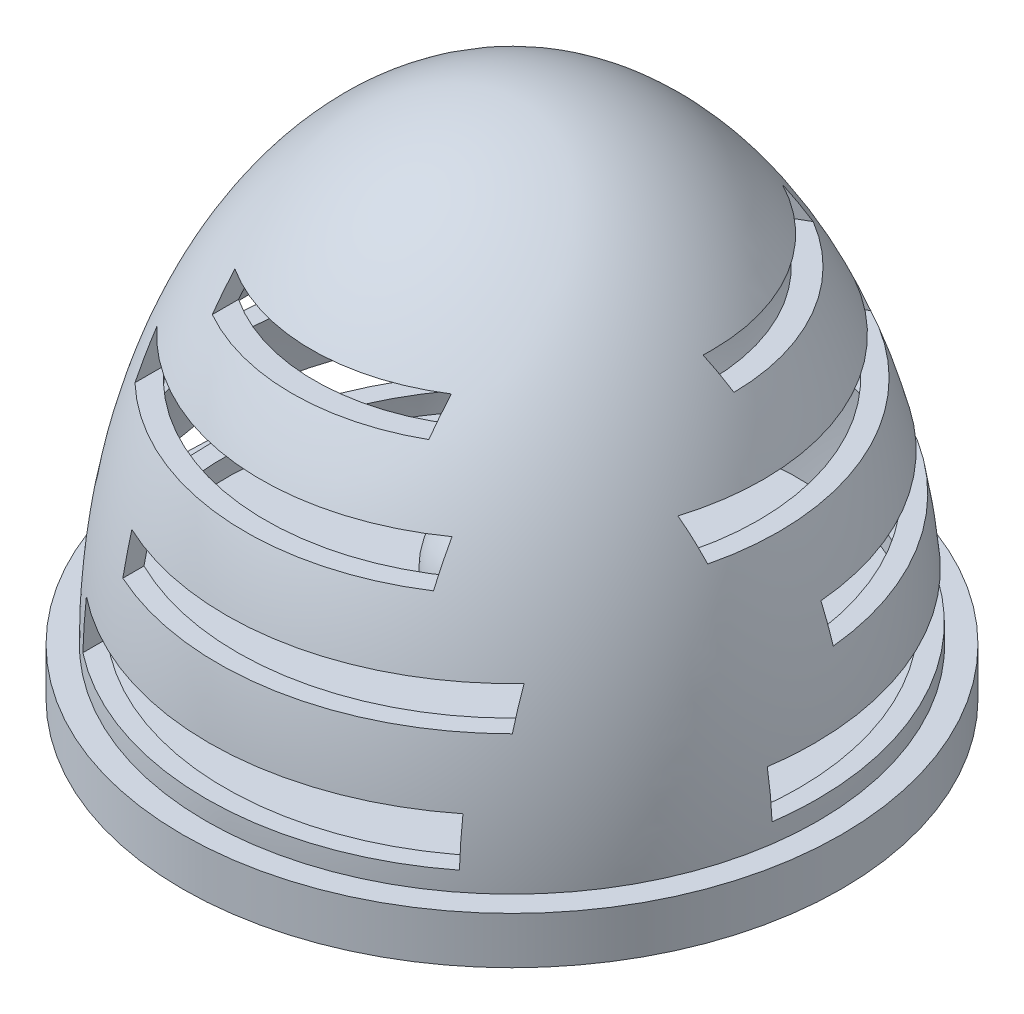
SolidWorks part; units mm, degrees
ref_plane "Piano frontale" through (0, 0, 0) normal (0, 0, 1) x (1, 0, 0)
ref_plane "Piano superiore" through (0, 0, 0) normal (0, 1, 0) x (1, 0, 0)
ref_plane "Piano destro" through (0, 0, 0) normal (1, 0, 0) x (0, 0, -1)
sketch "Schizzo1" plane through (0, 0, 0) normal (0, 1, 0) x (1, 0, 0)
  circle A0 centre (0, 0) radius 35
  dimension "D1" = 70
extrude "Estrusione-Estrusione1" add sketch "Schizzo1" along normal blind 5
sketch "Schizzo3" plane through (0, 5, 0) normal (0, 1, 0) x (1, 0, 0)
  line L0 (0, 49.3841) -> (0, -53.0263) construction
  line L1 (-54.1811, 0) -> (49.0863, 0) construction
  circle A0 centre (0, 0) radius 32.5
  dimension "D1" = 65
sketch "Schizzo4" plane through (0, 0, 0) normal (0, 0, 1) x (1, 0, 0)
  line L0 (32.5, 5) -> (-32.5, 5) construction
  line L1 (-54.1811, 5) -> (49.0863, 5) construction
  line L2 (0, 55) -> (0, 53)
  line L3 (30.5, 5) -> (32.5, 5)
  ellipse E0 centre (0, 5) end of major axis (0, 55) minor radius 32.5 (0, 55) -> (32.5, 5) cw
  spline S0 degree 1 poles (0, 53) (30.5, 5) knots 0 0 1 1 construction
  spline S1 degree 3 poles (0, 53) (1.9404, 53) (5.7713, 52.4189) (11.4211, 49.7948) (16.7188, 45.4458) (21.4383, 39.4955) (25.3526, 32.1643) (28.2812, 23.738) (30.0917, 14.569) (30.5, 8.1725) (30.5, 5) knots -1.570796 -1.570796 -1.570796 -1.570796 -1.374447 -1.178097 -0.981748 -0.785398 -0.589049 -0.392699 -0.19635 0 0 0 0
  dimension "D1" = 2
sketch "Schizzo6" plane through (0, 0, 0) normal (0, 0, 1) x (1, 0, 0)
  line L0 (0, 59.2821) -> (0, -7.287) construction
  line L1 (0, 23.503) -> (0, 5)
  arc A0 (0, 5) -> (2.3222, 18.6036) centre (0, 12) ccw
  arc A1 (2.3222, 18.6036) -> (0, 23.503) centre (0, 20.503) ccw
  point P8 (0, 5)
  dimension "D1" = 7
  dimension "D2" = 3
revolve "Rivoluzione1" add sketch "Schizzo6" angle 360 about L0
sketch "Schizzo7" plane through (0, 0, 0) normal (0, 0, 1) x (1, 0, 0)
  circle A0 centre (0, 20.9043) radius 1.5
  dimension "D1" = 3
extrude "Taglio-Estrusione1" cut sketch "Schizzo7" against normal mid plane 10 contours A0
revolve "Rivoluzione2" add sketch "Schizzo4" angle 360 about L2
sketch "Schizzo8" plane through (0, 0, 0) normal (0, 0, 1) x (1, 0, 0)
  line L0 (-12.9006, 18.8563) -> (22.0994, 18.8563)
  line L1 (-20, 7.022) -> (20, 7.022)
  line L2 (-20, 7.022) -> (-20, 12.022)
  line L3 (-20, 12.022) -> (20, 12.022)
  line L4 (20, 7.022) -> (20, 12.022)
  line L5 (-12.9006, 22.8563) -> (22.0994, 22.8563)
  line L6 (22.0994, 18.8563) -> (22.0994, 22.8563)
  line L7 (-12.9006, 18.8563) -> (-12.9006, 22.8563)
  line L8 (-11.5, 39.7564) -> (11.5, 39.7564)
  line L9 (-11.5, 42.7564) -> (11.5, 42.7564)
  line L10 (11.5, 39.7564) -> (11.5, 42.7564)
  line L11 (-11.5, 39.7564) -> (-11.5, 42.7564)
  line L12 (0, 63.9646) -> (0, -14.7502) construction
  line L13 (-19.5815, 33.514) -> (15.4185, 33.514)
  line L14 (15.4185, 29.514) -> (15.4185, 33.514)
  line L15 (-19.5815, 29.514) -> (-19.5815, 33.514)
  line L16 (-19.5815, 29.514) -> (15.4185, 29.514)
  dimension "D1" = 40
  dimension "D2" = 5
  dimension "D3" = 35
  dimension "D4" = 4
  dimension "D5" = 23
  dimension "D6" = 3
  dimension "D7" = 35
  dimension "D8" = 4
extrude "Taglio-Estrusione2" cut sketch "Schizzo8" against normal blind 25 from offset 40
pattern_circular "RipetizioneCircolare1" count 3 over 360 about axis through (0, 0, 0) along (0, 1, 0) of "Taglio-Estrusione2"
sketch "Schizzo10" plane through (0, 0, 0) normal (1, 0, 0) x (0, 0, -1)
  circle A0 centre (0, 20.9043) radius 1.5
  dimension "D1" = 3
extrude "Taglio-Estrusione3" cut sketch "Schizzo10" against normal mid plane 10 contours A0
